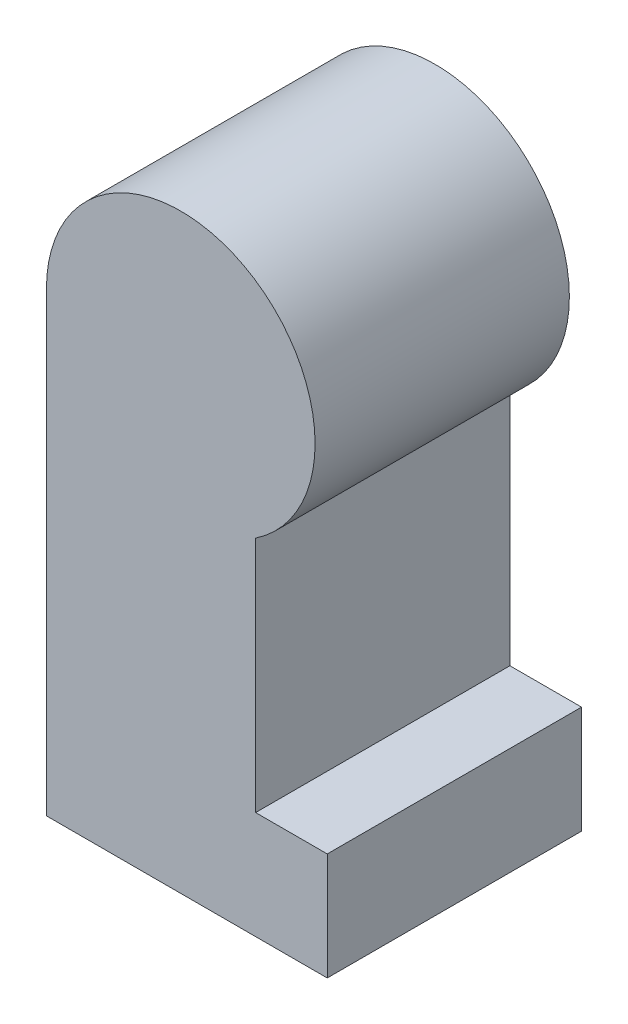
SolidWorks part; units mm, degrees
ref_plane "Front Plane" through (0, 0, 0) normal (0, 0, 1) x (1, 0, 0)
ref_plane "Top Plane" through (0, 0, 0) normal (0, 1, 0) x (1, 0, 0)
ref_plane "Right Plane" through (0, 0, 0) normal (1, 0, 0) x (0, 0, -1)
sketch "Sketch1" plane through (0, 0, 0) normal (0, 0, 1) x (1, 0, 0)
  line L0 (-95.25, 0) -> (-95.25, -323.85)
  line L1 (-95.25, -323.85) -> (103.886, -323.85)
  line L2 (53.086, -247.65) -> (53.086, -79.085)
  line L3 (103.886, -323.85) -> (103.886, -247.65)
  line L4 (103.886, -247.65) -> (53.086, -247.65)
  arc A0 (53.086, -79.085) -> (-95.25, 0) centre (0, 0) ccw
  dimension "D1" = 190.5
  dimension "D2" = 323.85
  dimension "D3" = 199.136
  dimension "D4" = 76.2
  dimension "D5" = 50.8
extrude "Boss-Extrude1" add sketch "Sketch1" along normal blind 180.34
sketch "Sketch2" plane through (0, 0, 0) normal (0, 0, -1) x (-1, 0, 0)
  circle A0 centre (0, 0) radius 38.1
  dimension "D1" = 76.2
extrude "Cut-Extrude1" cut sketch "Sketch2" against normal blind 101.6
sketch "Sketch3" plane through (0, -323.85, 0) normal (0, -1, 0) x (1, 0, 0)
  line L0 (-95.25, 180.34) -> (-95.25, 0) construction
  line L1 (-95.25, 180.34) -> (103.886, 180.34) construction
  circle A0 centre (4.318, 90.17) radius 61.722
  dimension "D1" = 123.444
  dimension "D2" = 99.568
  dimension "D3" = 90.17
extrude "Cut-Extrude2" cut sketch "Sketch3" against normal blind 50.8
sketch "Sketch4" plane through (-95.25, 0, 0) normal (-1, 0, 0) x (0, 0, 1)
  line L0 (0, 0) -> (0, -323.85) construction
  line L1 (180.34, -323.85) -> (0, -323.85) construction
  circle A0 centre (90.17, -209.55) radius 61.722
  circle A1 centre (90.17, -9.906) radius 61.722
  dimension "D1" = 123.444
  dimension "D2" = 90.17
  dimension "D3" = 114.3
  dimension "D4" = 2
extrude "Cut-Extrude3" cut sketch "Sketch4" against normal blind 50.8
